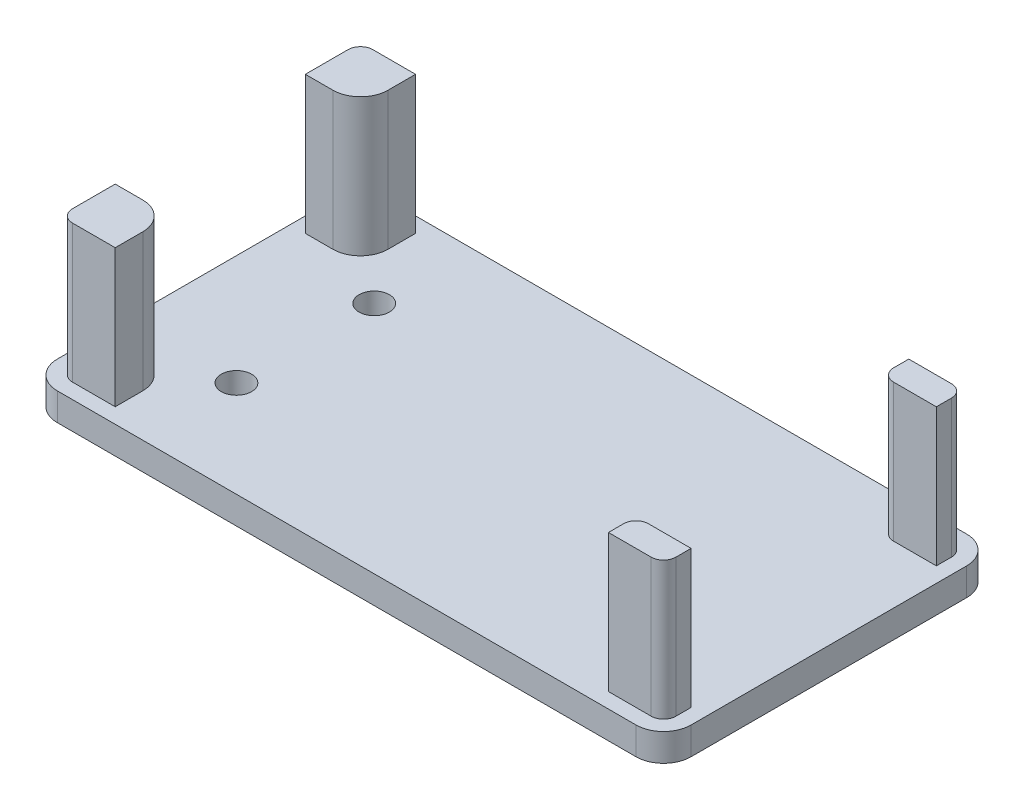
SolidWorks part; units mm, degrees
ref_plane "Front Plane" through (0, 0, 0) normal (0, 0, 1) x (1, 0, 0)
ref_plane "Top Plane" through (0, 0, 0) normal (0, 1, 0) x (1, 0, 0)
ref_plane "Right Plane" through (0, 0, 0) normal (1, 0, 0) x (0, 0, -1)
sketch "Sketch1" plane through (0, 0, 0) normal (0, 1, 0) x (1, 0, 0)
  line L1 (0, 0) -> (111.76, 0)
  line L2 (0, 0) -> (0, 60.96)
  line L3 (0, 60.96) -> (111.76, 60.96)
  line L4 (111.76, 0) -> (111.76, 60.96)
  dimension "D1" = 60.96
  dimension "D2" = 111.76
extrude "Boss-Extrude1" add sketch "Sketch1" along normal blind 5.08
fillet "Fillet1" radius 5.08 4 edges at (0, 2.54, -60.96) (111.76, 2.54, -60.96) (111.76, 2.54, 0) (0, 2.54, 0)
sketch "Sketch2" plane through (0, 5.08, 0) normal (0, 1, 0) x (1, 0, 0)
  line L0 (58.42, 60.96) -> (58.42, 0) construction
  line L1 (2.794, 58.166) -> (12.954, 58.166)
  line L2 (2.794, 58.166) -> (2.794, 48.006)
  line L3 (2.794, 48.006) -> (12.954, 48.006)
  line L4 (12.954, 58.166) -> (12.954, 48.006)
  line L7 (0, 30.48) -> (111.76, 30.48) construction
  line L8 (0, 55.88) -> (0, 5.08) construction
  line L9 (111.76, 5.08) -> (111.76, 55.88) construction
  line L18 (12.954, 2.794) -> (12.954, 12.954)
  line L19 (2.794, 12.954) -> (12.954, 12.954)
  line L20 (2.794, 2.794) -> (2.794, 12.954)
  line L21 (2.794, 2.794) -> (12.954, 2.794)
  line L30 (106.68, 60.96) -> (5.08, 60.96) construction
  line L31 (5.08, 0) -> (106.68, 0) construction
  line L33 (103.886, 58.166) -> (114.046, 58.166)
  line L34 (103.886, 58.166) -> (103.886, 53.086)
  line L35 (103.886, 53.086) -> (114.046, 53.086)
  line L36 (114.046, 58.166) -> (114.046, 53.086)
  line L37 (103.886, 2.794) -> (114.046, 2.794)
  line L38 (103.886, 2.794) -> (103.886, 7.874)
  line L39 (103.886, 7.874) -> (114.046, 7.874)
  line L40 (114.046, 2.794) -> (114.046, 7.874)
  dimension "D1" = 2.794
  dimension "D2" = 2.794
  dimension "D3" = 10.16
  dimension "D4" = 10.16
  dimension "D5" = 58.42
  dimension "D6" = 55.626
  dimension "D7" = 10.16
  dimension "D8" = 5.08
  dimension "D9" = 5.08
  dimension "D10" = 2.794
  dimension "D11" = 2.794
sketch "Sketch3" plane through (0, 0, 0) normal (0, -1, 0) x (1, 0, 0)
  circle A0 centre (20.32, -17.78) radius 2.794
  circle A1 centre (20.32, -43.18) radius 2.794
  circle A2 centre (30.48, -30.48) radius 3.302
  dimension "D1" = 5.588
  dimension "D2" = 5.588
  dimension "D3" = 6.604
  dimension "D4" = 10.16
  dimension "D5" = 25.4
  dimension "D6" = 17.78
  dimension "D7" = 12.7
  dimension "D8" = 20.32
extrude "Cut-Extrude1" cut sketch "Sketch3" against normal up to next
sketch "Sketch5" plane through (0, 0, 0) normal (0, -1, 0) x (1, 0, 0)
  line L1 (106.68, 0) -> (116.84, 0)
  line L2 (106.68, 0) -> (106.68, -60.96)
  line L3 (106.68, -60.96) -> (116.84, -60.96)
  line L4 (116.84, 0) -> (116.84, -60.96)
  dimension "D1" = 10.16
extrude "Boss-Extrude2" add sketch "Sketch5" against normal blind 5.08
fillet "Fillet2" radius 5.08 2 edges at (116.84, 2.54, -60.96) (116.84, 2.54, 0)
extrude "Boss-Extrude5" add sketch "Sketch2" along normal blind 25.4
fillet "Fillet9" radius 2.286 6 edges at (114.046, 17.78, -2.794) (103.886, 17.78, -7.874) (114.046, 17.78, -58.166) (103.886, 17.78, -53.086) (2.794, 17.78, -2.794) (2.794, 17.78, -58.166)
fillet "Fillet10" radius 5.08 2 edges at (12.954, 17.78, -12.954) (12.954, 17.78, -48.006)
sketch "Sketch6" plane through (0, 5.08, 0) normal (0, 1, 0) x (1, 0, 0)
  circle A0 centre (30.48, 30.48) radius 6.9961
extrude "Boss-Extrude6" add sketch "Sketch6" against normal blind 5.08
